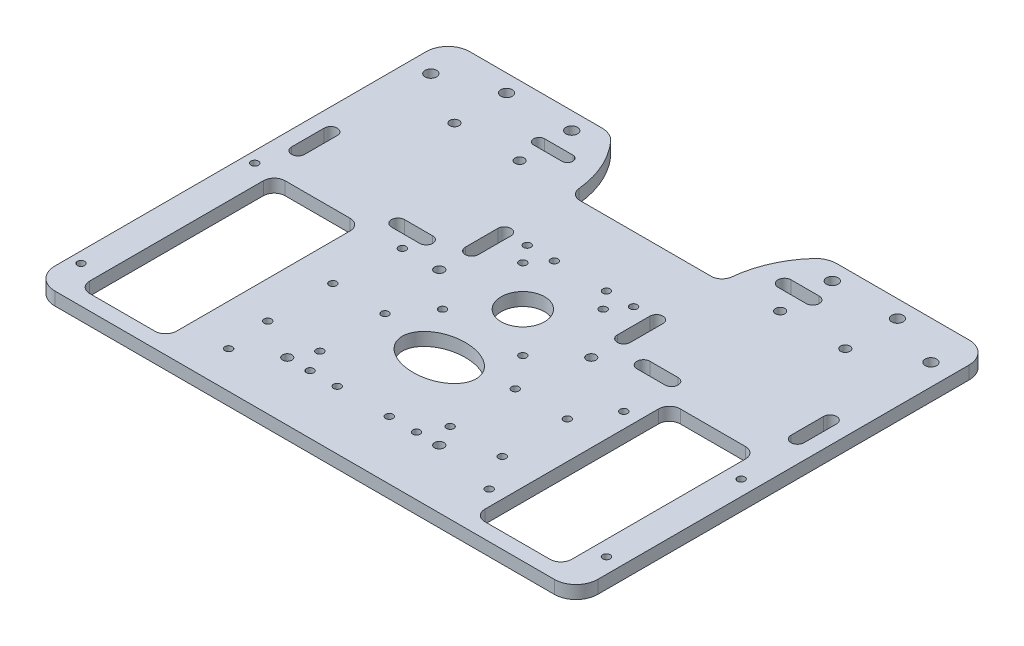
SolidWorks part; units mm, degrees
ref_plane "前视基准面" through (0, 0, 0) normal (0, 0, 1) x (1, 0, 0)
ref_plane "上视基准面" through (0, 0, 0) normal (0, 1, 0) x (1, 0, 0)
ref_plane "右视基准面" through (0, 0, 0) normal (1, 0, 0) x (0, 0, -1)
other "Configuration Table"
sketch "草图1" plane through (0, 0, 0) normal (0, 1, 0) x (1, 0, 0)
  line L0 (0, -1006) -> (0, 72) construction
  line L1 (0, 0) -> (-42, 0) construction
  line L2 (0, -52) -> (-49.0312, -52) construction
  line L3 (-52.3, -15) -> (-31.7, -15)
  line L4 (-54, -13.3) -> (-54, 13.3)
  line L5 (-52.3, 15) -> (-31.7, 15)
  line L6 (-30, -13.3) -> (-30, 13.3)
  line L7 (-52.938, -13.6725) -> (-31.062, 13.6725) construction
  line L8 (-52.938, 13.6725) -> (-31.062, -13.6725) construction
  line L9 (-106, -45) -> (-76, -45)
  line L10 (-111, -40) -> (-111, 40)
  line L11 (-106, 45) -> (-76, 45)
  line L13 (-111, -45) -> (-71, 45) construction
  line L14 (-111, 45) -> (-71, -45) construction
  line L15 (-115, -52) -> (0, -52)
  line L16 (0, -52) -> (115, -52)
  line L17 (54, 15) -> (30, -15) construction
  line L18 (-118, -45) -> (-76, -45)
  line L22 (-18.5, 30) -> (18.5, 30)
  line L23 (-18.5, 30) -> (-18.5, 67)
  line L24 (-18.5, 67) -> (18.5, 67)
  line L25 (18.5, 30) -> (18.5, 67)
  line L26 (-18.5, 30) -> (18.5, 67) construction
  line L27 (-18.5, 67) -> (18.5, 30) construction
  line L28 (54, -15) -> (30, 15) construction
  line L29 (30, -15) -> (30, 15)
  line L30 (54, 15) -> (30, 15)
  line L31 (54, -15) -> (54, 15)
  line L32 (54, -15) -> (30, -15)
  line L33 (111, 45) -> (71, -45) construction
  line L34 (111, -45) -> (71, 45) construction
  line L35 (71, -40) -> (71, 40)
  line L36 (106, 45) -> (76, 45)
  line L37 (111, -40) -> (111, 40)
  line L38 (106, -45) -> (76, -45)
  line L40 (118, -31) -> (64, -31)
  line L41 (118, -31) -> (118, 31)
  line L42 (118, 31) -> (64, 31)
  line L43 (64, -31) -> (64, 31)
  line L44 (118, -31) -> (64, 31) construction
  line L45 (118, 31) -> (64, -31) construction
  line L49 (0, -0.85) -> (0, 46.4975) construction
  line L50 (0, -25) -> (-12, -25)
  line L51 (-12, -25) -> (-24.5, -25)
  line L68 (-71, 40) -> (-71, -40)
  line L76 (0, 75) -> (-12, 75)
  line L77 (-12, 75) -> (-24.5, 75)
  line L78 (-125, -42) -> (-125, 129)
  line L79 (-60, 131) -> (-115.1492, 121.2757) construction
  line L81 (125, 129) -> (125, -42)
  line L82 (-60, 131) -> (-90, 131)
  line L85 (-35, -25) -> (35, -25)
  line L88 (-35, -25) -> (-35, 45)
  line L91 (-35, 45) -> (35, 45)
  line L94 (35, -25) -> (35, 45)
  line L97 (-35, -25) -> (35, 45) construction
  line L100 (-35, 45) -> (35, -25) construction
  line L103 (-30.2455, 105) -> (30.2455, 105)
  line L108 (-35, 121.9331) -> (-35, 72.4522) construction
  line L109 (-35, 60) -> (-35, 75) construction
  line L110 (-38, 60) -> (-38, 75)
  line L111 (-50, 119) -> (-63, 119) construction
  line L113 (-32, 60) -> (-32, 75)
  line L115 (-63, 54) -> (-50, 54) construction
  line L118 (63, 54) -> (50, 54) construction
  line L124 (63, 57) -> (50, 57)
  line L129 (0, 238) -> (158.7337, 238) construction
  line L130 (-115, 75) -> (-115, 60) construction
  line L131 (-112, 75) -> (-112, 60)
  line L132 (-118, 75) -> (-118, 60)
  line L133 (-50, 116.5) -> (-63, 116.5)
  line L136 (-115, 139) -> (-54.1558, 139)
  line L137 (63, 51) -> (50, 51)
  line L140 (115, 139) -> (54.1558, 139)
  line L141 (115, 75) -> (115, 60) construction
  line L142 (112, 75) -> (112, 60)
  line L143 (118, 75) -> (118, 60)
  line L144 (35, 60) -> (35, 75) construction
  line L145 (38, 60) -> (38, 75)
  line L146 (32, 60) -> (32, 75)
  line L147 (50, 119) -> (63, 119) construction
  line L150 (-50, 121.5) -> (-63, 121.5)
  line L155 (0, 200) -> (46.7563, 200) construction
  line L161 (-63, 57) -> (-50, 57)
  line L162 (-63, 51) -> (-50, 51)
  line L164 (-120, -35) -> (-52, -35)
  line L165 (-120, -35) -> (-120, 45)
  line L166 (-120, 45) -> (-52, 45)
  line L167 (-52, -35) -> (-52, 45)
  line L170 (50, 122) -> (63, 122)
  line L171 (50, 116) -> (63, 116)
  line L173 (-90, 131) -> (-60, 131)
  line L174 (-90, 131) -> (-90, 107)
  line L175 (-90, 107) -> (-60, 107)
  line L176 (-60, 131) -> (-60, 107)
  circle A0 centre (-54, 15) radius 1.7
  circle A1 centre (-30, 15) radius 1.7
  circle A2 centre (-30, -15) radius 1.7
  circle A3 centre (-54, -15) radius 1.7
  circle A8 centre (-18.5, 67) radius 1.7
  circle A9 centre (18.5, 67) radius 1.7
  circle A10 centre (18.5, 30) radius 1.7
  circle A11 centre (-18.5, 30) radius 1.7
  arc A12 (-106, -45) -> (-111, -40) centre (-106, -40) cw
  arc A13 (-76, -45) -> (-71, -40) centre (-76, -40) ccw
  arc A14 (-71, 40) -> (-76, 45) centre (-76, 40) ccw
  arc A15 (-111, 40) -> (-106, 45) centre (-106, 40) cw
  circle A16 centre (54, -15) radius 1.7
  circle A17 centre (30, -15) radius 1.7
  circle A18 centre (30, 15) radius 1.7
  circle A19 centre (54, 15) radius 1.7
  arc A20 (111, 40) -> (106, 45) centre (106, 40) ccw
  arc A21 (71, 40) -> (76, 45) centre (76, 40) cw
  arc A22 (76, -45) -> (71, -40) centre (76, -40) cw
  arc A23 (106, -45) -> (111, -40) centre (106, -40) ccw
  circle A24 centre (64, 31) radius 1.7
  circle A25 centre (118, 31) radius 1.7
  circle A26 centre (118, -31) radius 1.7
  circle A27 centre (64, -31) radius 1.7
  circle A32 centre (-24.5, -25) radius 1.7
  circle A33 centre (-12, -25) radius 1.7
  circle A34 centre (12, -25) radius 1.7
  circle A35 centre (24.5, -25) radius 1.7
  arc A66 (-125, -42) -> (-115, -52) centre (-115, -42) ccw
  arc A67 (115, -52) -> (125, -42) centre (115, -42) ccw
  circle A94 centre (-12, 75) radius 1.7
  circle A95 centre (-24.5, 75) radius 1.7
  circle A96 centre (-35, 45) radius 2.15
  circle A97 centre (35, 45) radius 2.15
  circle A98 centre (35, -25) radius 2.15
  circle A99 centre (-35, -25) radius 2.15
  arc A100 (-38, 60) -> (-32, 60) centre (-35, 60) ccw
  arc A101 (-32, 75) -> (-38, 75) centre (-35, 75) ccw
  arc A102 (-112, 75) -> (-118, 75) centre (-115, 75) ccw
  arc A103 (-118, 60) -> (-112, 60) centre (-115, 60) ccw
  arc A106 (-35.2215, 109.5101) -> (-46.6967, 135.6605) centre (-81.0333, 105) ccw
  arc A107 (-54.1558, 139) -> (-46.6967, 135.6605) centre (-54.1558, 129) cw
  arc A108 (-125, 129) -> (-115, 139) centre (-115, 129) cw
  circle A109 centre (12, 75) radius 1.7
  circle A110 centre (24.5, 75) radius 1.7
  arc A113 (125, 129) -> (115, 139) centre (115, 129) ccw
  arc A114 (54.1558, 139) -> (46.6967, 135.6605) centre (54.1558, 129) ccw
  arc A115 (35.2215, 109.5101) -> (46.6967, 135.6605) centre (81.0333, 105) cw
  arc A116 (112, 75) -> (118, 75) centre (115, 75) cw
  arc A117 (118, 60) -> (112, 60) centre (115, 60) cw
  arc A118 (38, 60) -> (32, 60) centre (35, 60) cw
  arc A119 (32, 75) -> (38, 75) centre (35, 75) cw
  arc A125 (30.2455, 105) -> (35.2215, 109.5101) centre (30.2455, 110) ccw
  arc A126 (-30.2455, 105) -> (-35.2215, 109.5101) centre (-30.2455, 110) cw
  circle A127 centre (0, 48.5) radius 10
  circle A135 centre (-60, 131) radius 2.65
  circle A136 centre (-115.1492, 121.2757) radius 2.65
  circle A137 centre (-90, 131) radius 2.65
  arc A138 (-50, 116.5) -> (-50, 121.5) centre (-50, 119) ccw
  arc A139 (-63, 121.5) -> (-63, 116.5) centre (-63, 119) ccw
  circle A142 centre (115.1492, 121.2757) radius 2.65
  circle A143 centre (90, 131) radius 2.65
  circle A144 centre (60, 131) radius 2.65
  arc A145 (-63, 57) -> (-63, 51) centre (-63, 54) ccw
  arc A146 (-50, 51) -> (-50, 57) centre (-50, 54) ccw
  circle A147 centre (-120, 45) radius 1.7
  circle A148 centre (-52, 45) radius 1.7
  circle A149 centre (-52, -35) radius 1.7
  circle A150 centre (-120, -35) radius 1.7
  arc A153 (63, 57) -> (63, 51) centre (63, 54) cw
  arc A154 (50, 51) -> (50, 57) centre (50, 54) cw
  arc A155 (50, 122) -> (50, 116) centre (50, 119) ccw
  arc A156 (63, 116) -> (63, 122) centre (63, 119) ccw
  circle A157 centre (-90, 107) radius 2.15
  circle A158 centre (-60, 107) radius 2.15
  circle A159 centre (60, 107) radius 2.15
  circle A160 centre (90, 107) radius 2.15
  ellipse E0 centre (0, 10) end of major axis (-17, 10) minor radius 12
  point P14 (-91, 0)
  point P31 (0, 48.5)
  point P76 (91, 0)
  point P77 (91, 0)
  point P84 (42, 0)
  point P89 (56.5, 54)
  point P110 (-67, 22)
  point P111 (56.5, 119)
  point P113 (-71, -28.5)
  point P114 (-67, 33)
  point P116 (-68, -38.4641)
  point P120 (-68, -18.5359)
  point P123 (0, 10)
  point P142 (-35, 67.5)
  point P147 (-115, 67.5)
  point P158 (-56.5, 119)
  point P178 (0, 0)
  point P189 (-125, -52)
  point P192 (125, -52)
  point P195 (115, 67.5)
  point P202 (35, 67.5)
  point P227 (35, 105)
  point P230 (-35, 105)
  point P237 (-56.5, 54)
  dimension "D4" = 3.4
  dimension "D9" = 8
  dimension "D15" = 68
  dimension "D21" = 3.4
  dimension "D23" = 5
  dimension "D28" = 3.4
  dimension "D33" = 3.4
  dimension "D34" = 12
  dimension "D37" = 3.4
  dimension "D38" = 3.4
  dimension "D39" = 30
  dimension "D40" = 60
  dimension "D41" = 17
  dimension "D29" = 12
  dimension "D43" = 75
  dimension "D49" = 30
  dimension "D50" = 55
  dimension "D52" = 5.3
  dimension "D53" = 5.3
  dimension "D55" = 10
  dimension "D59" = 90
  dimension "D60" = 20
  dimension "D62" = 191
  dimension "D66" = 70
  dimension "D67" = 65
  dimension "D71" = 4.3
  dimension "D69" = 60
  dimension "D73" = 5.5
  dimension "D32" = 3.4
  dimension "D48" = 4.3
  dimension "D61" = 56
  dimension "D63" = 10
  dimension "D64" = 20
  dimension "D57" = 65
  dimension "D70" = 24
  dimension "D74" = 4.3
  dimension "D76" = 5
  dimension "D22" = 17
  dimension "D58" = 5.3
  dimension "D17" = 3.4
  dimension "D68" = 26
  dimension "D1" = 24
  dimension "D2" = 30
  dimension "D6" = 40
  dimension "D7" = 90
  dimension "D8" = 0
  dimension "D10" = 80
  dimension "D11" = 125
  dimension "D12" = 125
  dimension "D13" = 0
  dimension "D14" = 14
  dimension "D16" = 5
  dimension "D18" = 7
  dimension "D19" = 37
  dimension "D20" = 37
  dimension "D24" = 7
  dimension "D25" = 54
  dimension "D26" = 62
  dimension "D27" = 0
  dimension "D30" = 24.5
  dimension "D31" = 5
  dimension "D35" = 24.5
  dimension "D36" = 27
  dimension "D42" = 16
  dimension "D44" = 127
  dimension "D45" = 10
  dimension "D46" = 70
  dimension "D47" = 70
  dimension "D51" = 15
  dimension "D54" = 30
  dimension "D56" = 35
  dimension "D65" = 80
  dimension "D72" = 34
  dimension "D79" = 290
  dimension "D80" = 129
  dimension "D81" = 42
  dimension "D82" = 95
  dimension "D83" = 38
  dimension "D85" = 95
extrude "凸台-拉伸2" add sketch "草图1" along normal blind 6 contours L103 A126 A106 A107 L136 A108 L78 A66 L15 L16 A67 L81 A113 L140 A114 A115 A125 A159 A158 L175 A157 L174 A137 L173 A135 L176 L150 A138 L133 A156 L171 A155 L170 A150 L165 A147 L166 L11 A148 L167 L5 L88 A96 L91 L23 | A158 L176 L133 A139 L150 A135 L173 A137 L174 A157 L175 | A150 L164 L10 A15 L166 A147 L165 | A149 L167 L3 A3 L4 A0 L5 A148 L166 A14 L68 L164 | A3 L3 L167 L5 A0 L4 | L167 L3 L88 L5 | A2 L6 A1 L5 L88 L3 | A99 L85 A32 A33 L50 A34 A35 A98 L94 L32 A17 L29 A18 L30 A97 L91 L25 A10 L22 A11 L23 A96 L88 L5 A1 L6 A2 L3 E0 | L31 A19 L30 L94 L32 A16 | L30 A18 L29 A17 L32 L94 | A127 L91 L25 A9 L24 A8 L23 | A127 L91 L23 A11 L22 A10 L25 | A27 L40 L35 L42 A24 L43 | A26 L41 A25 L42 L37 L40
